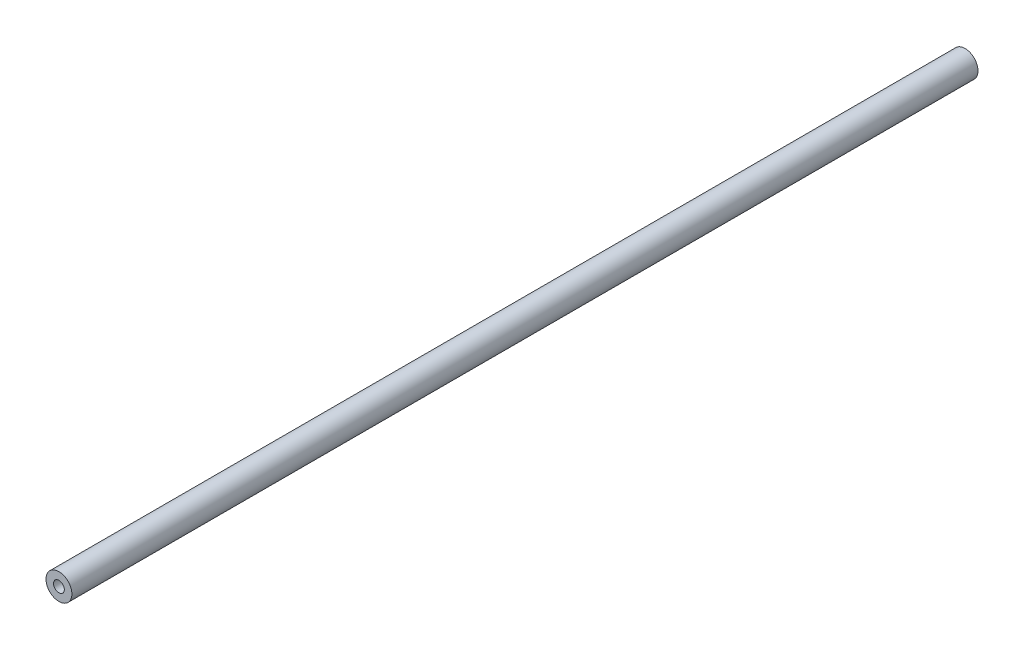
SolidWorks part; units mm, degrees
material "铸造碳钢"
ref_plane "前视基准面" through (0, 0, 0) normal (0, 0, 1) x (1, 0, 0)
ref_plane "上视基准面" through (0, 0, 0) normal (0, 1, 0) x (1, 0, 0)
ref_plane "右视基准面" through (0, 0, 0) normal (1, 0, 0) x (0, 0, -1)
sketch "草图1" plane through (0, 0, 0) normal (0, 0, 1) x (1, 0, 0)
  circle A0 centre (0, 0) radius 0.0005
  circle A1 centre (0, 0) radius 6
  dimension "D1" = 12
  dimension "D2" = 0.001
extrude "凸台-拉伸1" add sketch "草图1" against normal blind 420
sketch "草图2" plane through (0, 0, 0) normal (0, 0, 1) x (1, 0, 0)
  circle A0 centre (0, 0) radius 2.5
  dimension "D1" = 5
extrude "切除-拉伸1" cut sketch "草图2" against normal through all
